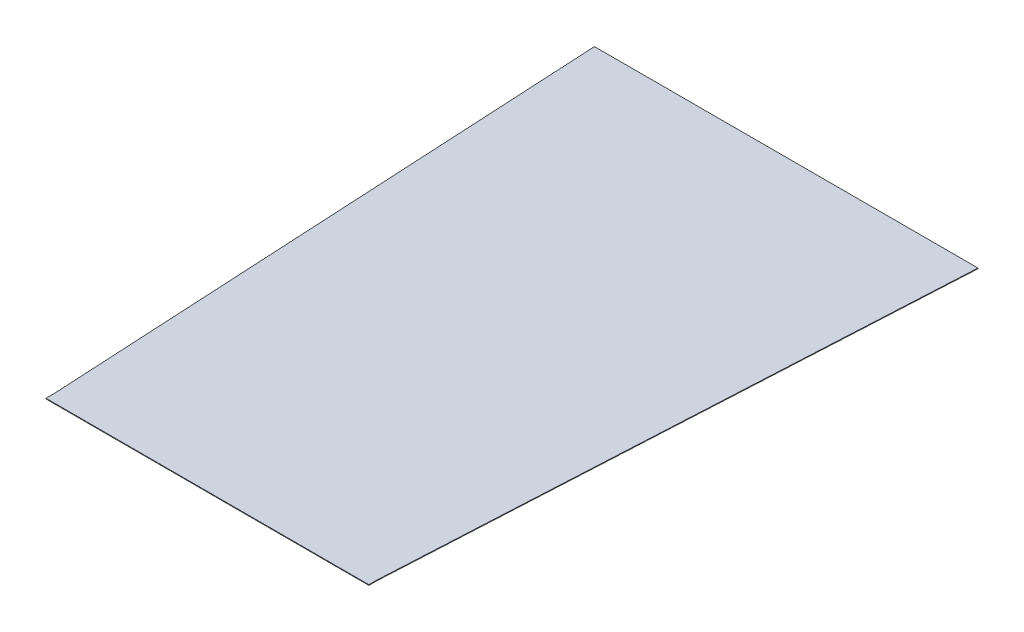
SolidWorks part; units mm, degrees
material "5052-O"
ref_plane "Front Plane" through (0, 0, 0) normal (0, 0, 1) x (1, 0, 0)
ref_plane "Top Plane" through (0, 0, 0) normal (0, 1, 0) x (1, 0, 0)
ref_plane "Right Plane" through (0, 0, 0) normal (1, 0, 0) x (0, 0, -1)
sketch "Sketch1" plane through (0, 0, 0) normal (0, 1, 0) x (1, 0, 0)
  line L0 (-247.7, 0) -> (247.7, 0)
  line L1 (-55, 0) -> (55, 0) construction
  line L2 (247.7, 0) -> (247.7, 12.02)
  line L3 (-247.7, 0) -> (-247.7, 12.02)
  line L4 (247.7, 12.02) -> (294.245, 888.0343)
  line L5 (-247.7, 12.02) -> (-294.245, 888.0343)
  line L6 (-294.245, 888.0343) -> (294.245, 888.0343)
  point P6 (0, 0)
  point P8 (0, 888.0343)
  point P10 (0, 0)
  dimension "D1" = 495.4
  dimension "D2" = 12.02
  dimension "D3" = 588.49
  dimension "D4" = 877.25
extrude "Front Floor Closeout" add sketch "Sketch1" along normal blind 1
